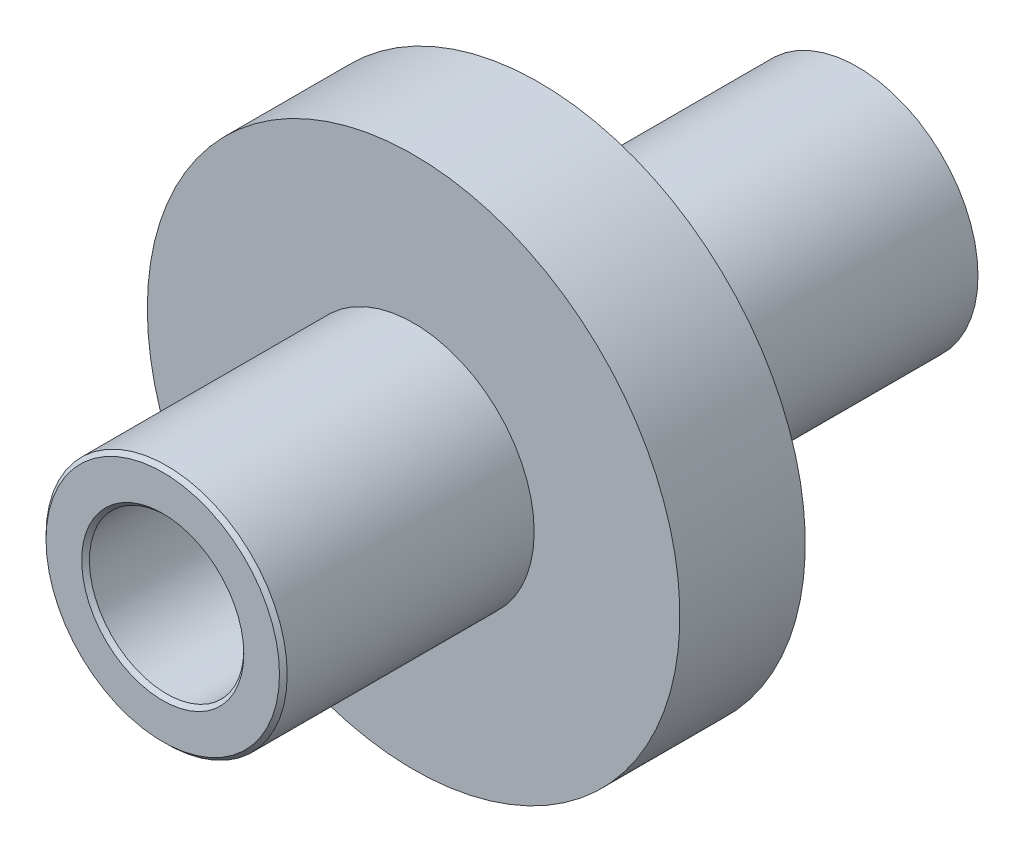
SolidWorks part; units mm, degrees
ref_plane "Спереди" through (0, 0, 0) normal (0, 0, 1) x (1, 0, 0)
ref_plane "Сверху" through (0, 0, 0) normal (0, 1, 0) x (1, 0, 0)
ref_plane "Справа" through (0, 0, 0) normal (1, 0, 0) x (0, 0, -1)
sketch "Эскиз1" plane through (0, 0, 0) normal (0, 0, 1) x (1, 0, 0)
  circle A0 centre (0, 0) radius 13.8
  circle A1 centre (0, 0) radius 4
extrude "Бобышка-Вытянуть1" add sketch "Эскиз1" along normal blind 6.5
sketch "Эскиз2" plane through (0, 0, 6.5) normal (0, 0, 1) x (1, 0, 0)
  circle A0 centre (0, 0) radius 4
  circle A1 centre (0, 0) radius 6.25
extrude "Бобышка-Вытянуть2" add sketch "Эскиз2" along normal blind 13 and the other way blind 23
sketch "Эскиз3" plane through (0, 0, -16.5) normal (0, 0, -1) x (-1, 0, 0)
  line L0 (-3.4641, -2) -> (3.4641, -2)
  arc A0 (-3.4641, -2) -> (3.4641, -2) centre (0, 0) ccw
extrude "Бобышка-Вытянуть3" add sketch "Эскиз3" against normal blind 8
chamfer "Фаска1" distance 0.2 angle 45 4 edges at (6.25, 0, 19.5) (4, 0, 19.5) (0, 4, -16.5) (0, -2, -16.5)
